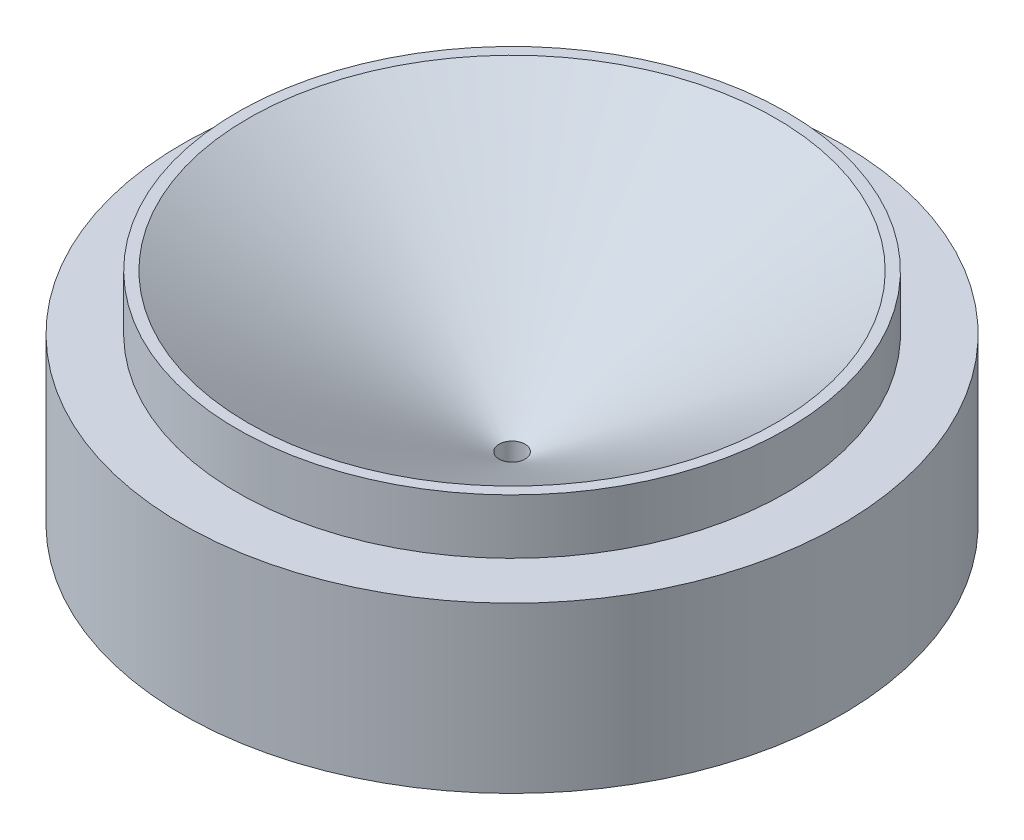
SolidWorks part; units mm, degrees
ref_plane "Front Plane" through (0, 0, 0) normal (0, 0, 1) x (1, 0, 0)
ref_plane "Top Plane" through (0, 0, 0) normal (0, 1, 0) x (1, 0, 0)
ref_plane "Right Plane" through (0, 0, 0) normal (1, 0, 0) x (0, 0, -1)
sketch "Sketch1" plane through (0, 0, 0) normal (0, 0, 1) x (1, 0, 0)
  line L0 (0, -12.7) -> (30.5054, 6.35)
  line L1 (38.1, 0) -> (0, 0) construction
  line L2 (31.75, 0) -> (38.1, 0)
  line L3 (31.75, 6.35) -> (31.75, 0)
  line L4 (38.1, 0) -> (38.1, -19.05)
  line L5 (38.1, -19.05) -> (0, -19.05)
  line L8 (0, -19.05) -> (0, -12.7)
  line L10 (31.75, 6.35) -> (30.5054, 6.35)
  dimension "D2" = 31.75
  dimension "D3" = 6.35
  dimension "D4" = 19.05
  dimension "D5" = 38.1
  dimension "D6" = 19.05
  dimension "D8" = 30.5054
revolve "Revolve1" add sketch "Sketch1" angle 360 about L8
sketch "Sketch2" plane through (0, -19.05, 0) normal (0, -1, 0) x (1, 0, 0)
  circle A0 centre (0, 0) radius 1.5
  dimension "D1" = 3
extrude "Cut-Extrude1" cut sketch "Sketch2" against normal through all
